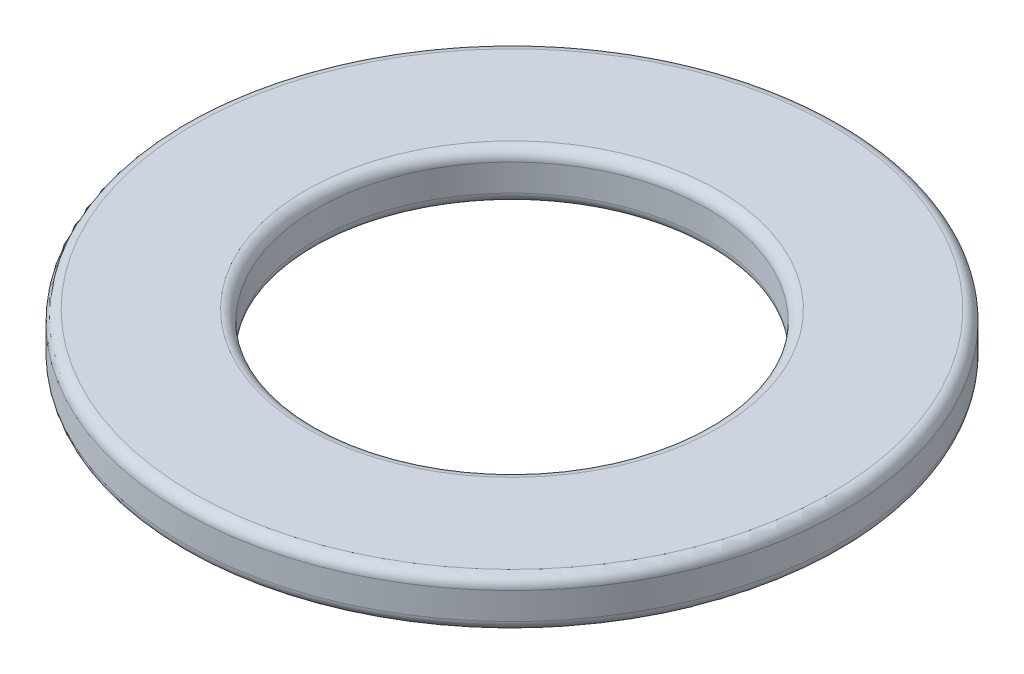
SolidWorks part; units mm, degrees
ref_plane "Спереди" through (0, 0, 0) normal (0, 0, 1) x (1, 0, 0)
ref_plane "Сверху" through (0, 0, 0) normal (0, 1, 0) x (1, 0, 0)
ref_plane "Справа" through (0, 0, 0) normal (1, 0, 0) x (0, 0, -1)
sketch "Эскиз1" plane through (0, 0, 0) normal (0, 1, 0) x (1, 0, 0)
  circle A0 centre (0, 0) radius 18.2
  circle A1 centre (0, 0) radius 30.7
extrude "Вытянуть1" add sketch "Эскиз1" along normal blind 4.5
fillet "Скругление1" radius 1 4 edges at (0, 0, 18.2) (0, 4.5, 18.2) (0, 0, 30.7) (0, 4.5, 30.7)
